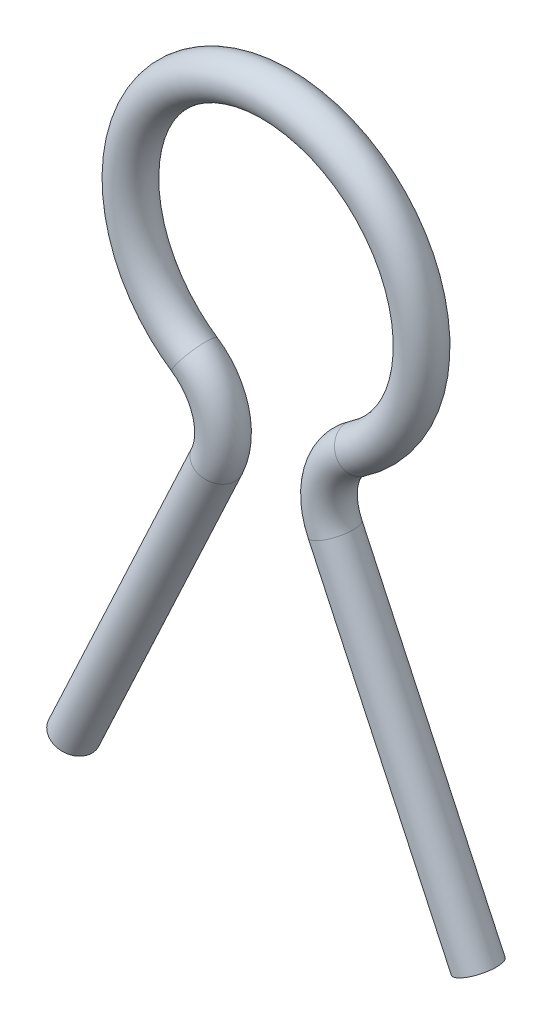
SolidWorks part; units mm, degrees
material "Brass"
ref_plane "Front Plane" through (0, 0, 0) normal (0, 0, 1) x (1, 0, 0)
ref_plane "Top Plane" through (0, 0, 0) normal (0, 1, 0) x (1, 0, 0)
ref_plane "Right Plane" through (0, 0, 0) normal (1, 0, 0) x (0, 0, -1)
sketch "Sketch1" plane through (0, 0, 0) normal (0, 0, 1) x (1, 0, 0)
  line L0 (0, 0) -> (-5.6207, 12.0537)
  line L1 (-10.2543, 12.0537) -> (-15.875, 0)
  line L2 (-7.9375, 19.969) -> (-7.9375, 2.5532) construction
  arc A0 (-4.7399, 15.2323) -> (-11.1351, 15.2323) centre (-7.9375, 19.969) ccw
  arc A1 (-11.1351, 15.2323) -> (-10.2543, 12.0537) centre (-12.5563, 13.1271) cw
  arc A2 (-4.7399, 15.2323) -> (-5.6207, 12.0537) centre (-3.3187, 13.1271) ccw
  point P6 (0, 0)
  point P7 (0, 0)
  point P9 (0, 0)
  point P12 (-9.1659, 14.3876)
  point P15 (-6.7091, 14.3876)
  dimension "D1" = 5.715
  dimension "D8" = 2.54
  dimension "D2" = 15.875
  dimension "D3" = 15.875
  dimension "D4" = 25
  dimension "D5" = 25
  dimension "D6" = 7.9375
  dimension "D7" = 25.684
ref_plane "Plane1" through (0, 0, 0) normal (-0.4226, 0.9063, 0) x (0.9063, 0.4226, 0)
sketch "Sketch3" plane through (0, 0, 0) normal (-0.4226, 0.9063, 0) x (0.9063, 0.4226, 0)
  circle A0 centre (0, 0) radius 0.7874
  dimension "D1" = 1.5748
sweep "Sweep1" add profiles "Sketch3" path "Sketch1"
